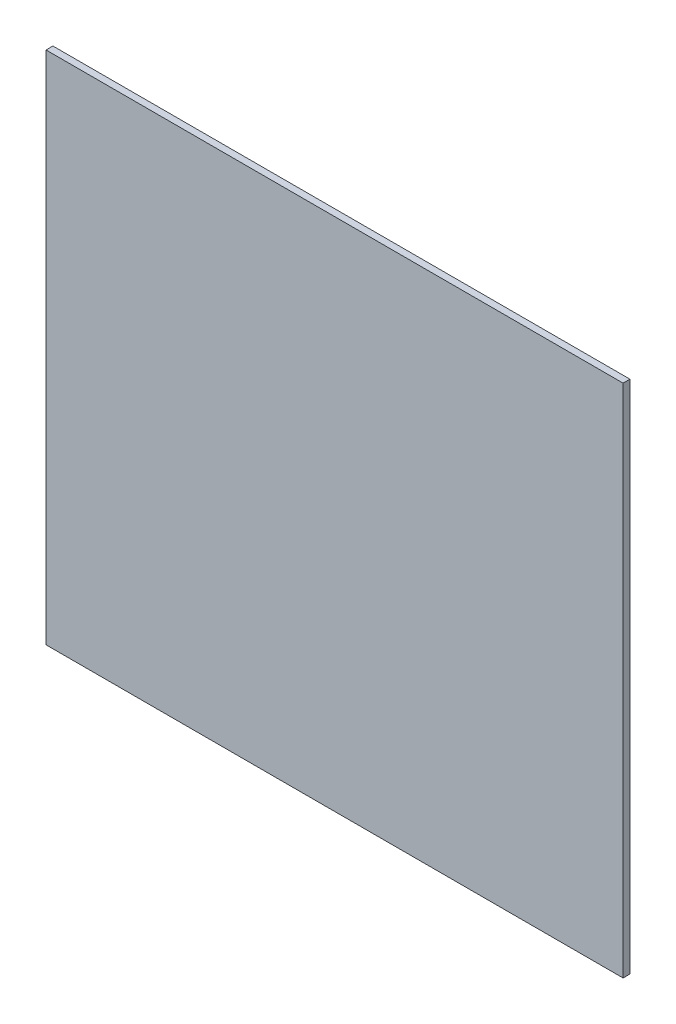
SolidWorks part; units mm, degrees
material "아크릴(내충격성)"
ref_plane "정면" through (0, 0, 0) normal (0, 0, 1) x (1, 0, 0)
ref_plane "윗면" through (0, 0, 0) normal (0, 1, 0) x (1, 0, 0)
ref_plane "우측면" through (0, 0, 0) normal (1, 0, 0) x (0, 0, -1)
sketch "스케치1" plane through (0, 0, 0) normal (0, 0, 1) x (1, 0, 0)
  line L1 (-210, 187.48) -> (210, 187.48)
  line L2 (-210, 187.48) -> (-210, -187.48)
  line L3 (-210, -187.48) -> (210, -187.48)
  line L4 (210, 187.48) -> (210, -187.48)
  line L5 (-210, 187.48) -> (210, -187.48) construction
  line L6 (-210, -187.48) -> (210, 187.48) construction
  point P0 (0, 0)
  dimension "D1" = 374.96
  dimension "D2" = 420
extrude "보스-돌출1" add sketch "스케치1" along normal blind 5
